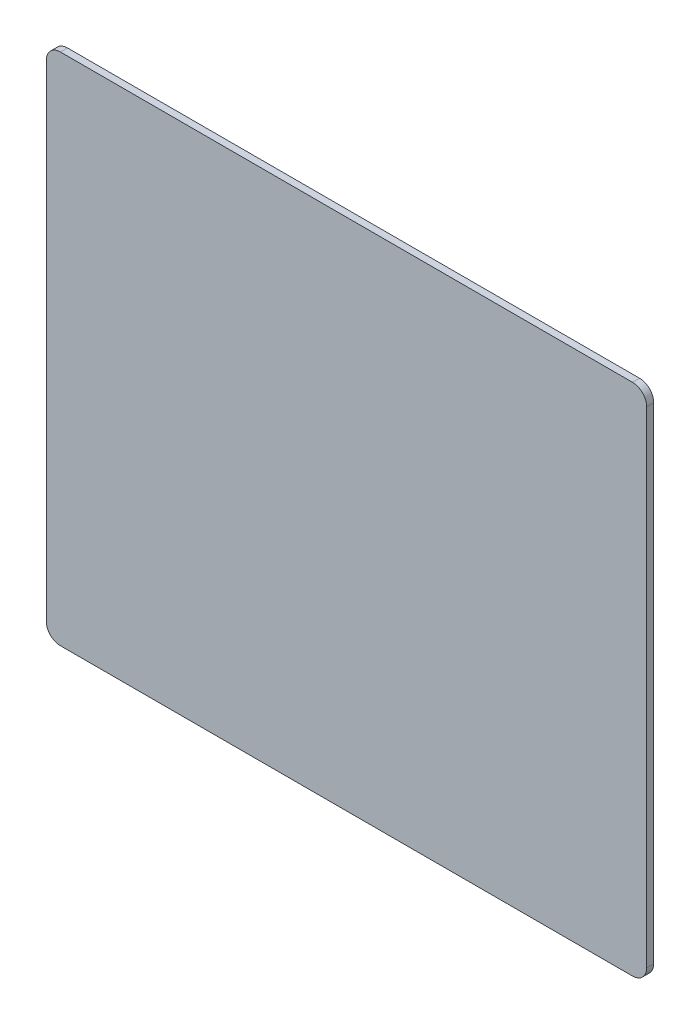
SolidWorks part; units mm, degrees
ref_plane "Plan de face" through (0, 0, 0) normal (0, 0, 1) x (1, 0, 0)
ref_plane "Plan de dessus" through (0, 0, 0) normal (0, 1, 0) x (1, 0, 0)
ref_plane "Plan de droite" through (0, 0, 0) normal (1, 0, 0) x (0, 0, -1)
sketch "Esquisse1" plane through (0, 0, 0) normal (0, 0, 1) x (1, 0, 0)
  line L1 (-40.5, 36.4) -> (40.5, 36.4)
  line L2 (-42.5, 34.4) -> (-42.5, -34.4)
  line L3 (-40.5, -36.4) -> (40.5, -36.4)
  line L4 (42.5, 34.4) -> (42.5, -34.4)
  line L5 (-42.5, 36.4) -> (42.5, -36.4) construction
  line L6 (-42.5, -36.4) -> (42.5, 36.4) construction
  arc A0 (-42.5, -34.4) -> (-40.5, -36.4) centre (-40.5, -34.4) ccw
  arc A1 (40.5, -36.4) -> (42.5, -34.4) centre (40.5, -34.4) ccw
  arc A2 (40.5, 36.4) -> (42.5, 34.4) centre (40.5, 34.4) cw
  arc A3 (-40.5, 36.4) -> (-42.5, 34.4) centre (-40.5, 34.4) ccw
  point P0 (0, 0)
  dimension "D3" = 2
  dimension "D1" = 85
  dimension "D2" = 72.8
extrude "Boss.-Extru.1" add sketch "Esquisse1" along normal blind 1
sketch "Esquisse2" plane through (0, 0, 0) normal (0, 0, -1) x (-1, 0, 0)
  line L0 (-35.5, 28.4) -> (-35.5, 19.4)
  line L1 (-35.5, 19.4) -> (-31.627, 18.4)
  line L2 (-31.627, 18.4) -> (-20.5, 18.4)
  line L3 (-20.5, 18.4) -> (-20.5, 28.4)
  line L4 (-20.5, 28.4) -> (-35.5, 28.4)
  line L5 (-42.5, -34.4) -> (-42.5, 34.4) construction
  line L6 (-40.5, 36.4) -> (40.5, 36.4) construction
  dimension "D1" = 15
  dimension "D2" = 10
  dimension "D3" = 9
  dimension "D4" = 4
  dimension "D5" = 7
  dimension "D6" = 8
extrude "Boss.-Extru.2" add sketch "Esquisse2" along normal blind 0.2
pattern_linear "Répétition linéaire1" count 4 spacing 19 along (-1, 0, 0) count 5 spacing 12 along (0, -1, 0) skipping (3, 3), (3, 4) of "Boss.-Extru.2"
sketch "Esquisse3" plane through (0, 0, 0) normal (0, 0, -1) x (-1, 0, 0)
  line L1 (21.5, -7.6) -> (36.5, -7.6) construction
  line L2 (36.5, -7.6) -> (36.5, -17.6) construction
  line L3 (36.5, -17.6) -> (21.5, -17.6) construction
  line L4 (21.5, -17.6) -> (21.5, -7.6) construction
  line L5 (36.5, -5.6) -> (36.5, 4.4) construction
  line L6 (21.5, 4.4) -> (21.5, -4.6) construction
  line L7 (6.373, -17.6) -> (17.5, -17.6) construction
  line L8 (17.5, -7.6) -> (2.5, -7.6) construction
  ellipse E0 centre (29, -12.6) end of major axis (36.5, -12.6) minor radius 5
  point P18 (36.5, -13.4665)
extrude "Boss.-Extru.3" add sketch "Esquisse3" along normal blind 0.2
pattern_linear "Répétition linéaire2" count 2 spacing 12 along (0, -1, 0) of "Boss.-Extru.3"
sketch "Esquisse4" plane through (0, 0, -0.2) normal (0, 0, -1) x (-1, 0, 0)
  line L0 (-20.5, 18.4) -> (-20.5, 28.4) construction
  line L1 (-31.75, 20.4) -> (-20.5, 20.4) construction
  line L2 (-31.75, 20.4) -> (-31.75, 33.0905) construction
  line L4 (-20.5, 28.4) -> (-35.5, 28.4) construction
  line L5 (-12.75, 20.4) -> (-3.304, 20.4) construction
  line L6 (-1.5, 28.4) -> (-16.5, 28.4) construction
  line L7 (7, 20.4) -> (15.4189, 20.4) construction
  line L8 (27, 18.9) -> (33.7413, 18.9) construction
  line L9 (-30, 8.4) -> (-22.7278, 8.4) construction
  line L10 (-30, -3.6) -> (-22.7278, -3.6) construction
  line L11 (-11, 8.4) -> (-3.304, 8.4) construction
  line L12 (8, 8.4) -> (15.4189, 8.4) construction
  line L13 (24.3298, 8.4) -> (33.7413, 8.4) construction
  line L14 (24.3298, -3.6) -> (33.7413, -3.6) construction
  line L15 (8, -3.6) -> (14.3175, -3.6) construction
  line L16 (-11, -3.6) -> (-4.8059, -3.6) construction
  line L17 (-30, -15.6) -> (-22.7278, -15.6) construction
  line L18 (-11, -15.6) -> (-3.304, -15.6) construction
  line L19 (8, -15.6) -> (14.3175, -15.6) construction
  line L20 (-31.75, -27.6) -> (-23.9293, -27.6) construction
  line L21 (23.5, -15.6) -> (35.7582, -15.6) construction
  line L22 (-11, -27.6) -> (-4.8059, -27.6) construction
  line L23 (6, -27.6) -> (14.3175, -27.6) construction
  line L24 (23.5, -26.6827) -> (31.8102, -26.6827) construction
  line L25 (17.5, 28.4) -> (2.5, 28.4) construction
  line L26 (36.5, 28.4) -> (21.5, 28.4) construction
  line L27 (36.5, 28.4) -> (21.5, 28.4) construction
  line L28 (-20.5, 16.4) -> (-35.5, 16.4) construction
  line L29 (-20.5, 4.4) -> (-35.5, 4.4) construction
  line L30 (-20.5, -7.6) -> (-35.5, -7.6) construction
  line L31 (-20.5, -19.6) -> (-35.5, -19.6) construction
  line L32 (-1.5, 16.4) -> (-16.5, 16.4) construction
  line L33 (17.5, 16.4) -> (2.5, 16.4) construction
  line L34 (28, 8.4) -> (28, 12.4)
  line L35 (28, 12.4) -> (26.5, 12.4)
  line L36 (26.5, 12.4) -> (29, 15.4)
  line L37 (29, 15.4) -> (31.5, 12.4)
  line L38 (31.5, 12.4) -> (30, 12.4)
  line L39 (30, 12.4) -> (30, 8.4)
  line L40 (30, 8.4) -> (28, 8.4)
  line L41 (36.5, 16.4) -> (21.5, 16.4) construction
  line L44 (28, 3.4) -> (28, -0.6)
  line L52 (28, -0.6) -> (26.5, -0.6)
  line L53 (26.5, -0.6) -> (29, -3.6)
  line L54 (29, -3.6) -> (31.5, -0.6)
  line L55 (31.5, -0.6) -> (30, -0.6)
  line L56 (30, -0.6) -> (30, 3.4)
  line L57 (30, 3.4) -> (28, 3.4)
  line L58 (-24, -23.6) -> (-24, -25.6)
  line L59 (-24, -25.6) -> (-28, -25.6)
  line L60 (-28, -25.6) -> (-28, -27.1)
  line L61 (-28, -27.1) -> (-31, -24.6)
  line L62 (-31, -24.6) -> (-28, -22.1)
  line L63 (-28, -22.1) -> (-28, -23.6)
  line L64 (-28, -23.6) -> (-24, -23.6)
  line L65 (6, -23.6) -> (6, -25.6)
  line L66 (6, -25.6) -> (10, -25.6)
  line L67 (10, -25.6) -> (10, -27.1)
  line L68 (10, -27.1) -> (13, -24.6)
  line L69 (13, -24.6) -> (10, -22.1)
  line L70 (10, -22.1) -> (10, -23.6)
  line L71 (10, -23.6) -> (6, -23.6)
  line L72 (-20.5, -19.6) -> (-35.5, -19.6) construction
  line L73 (-20.5, -29.6) -> (-20.5, -19.6) construction
  line L74 (17.5, -19.6) -> (2.5, -19.6) construction
  line L75 (36.5, 4.4) -> (21.5, 4.4) construction
  text T0 "F1" font "Century Gothic" height in points 22
  text T1 "F2" font "Century Gothic" height in points 22
  text T2 "#" font "Century Gothic" height in points 22
  text T3 "*" font "Century Gothic" height in points 22
  text T4 "1" font "Century Gothic" height in points 22
  text T5 "2" font "Century Gothic" height in points 22
  text T6 "3" font "Century Gothic" height in points 22
  text T7 "4" font "Century Gothic" height in points 22
  text T8 "5" font "Century Gothic" height in points 22
  text T9 "6" font "Century Gothic" height in points 22
  text T10 "7" font "Century Gothic" height in points 22
  text T11 "8" font "Century Gothic" height in points 22
  text T12 "9" font "Century Gothic" height in points 22
  text T13 "0" font "Century Gothic" height in points 22
  text T14 "Esc" font "Century Gothic" height in points 20
  text T15 "Ent" font "Century Gothic" height in points 20
  point P10 (-28, 28.4)
  point P14 (-9, 28.4)
  point P54 (10, 28.4)
  point P58 (29, 28.4)
  point P72 (-28, 16.4)
  point P75 (-9, 16.4)
  point P78 (10, 16.4)
  point P87 (29, 16.4)
  point P110 (0, 0)
  point P113 (-28, -19.6)
  point P116 (-20.5, -24.6)
  point P117 (-24, -24.6)
  point P118 (0, 0)
  point P119 (0, 0)
  point P122 (0, 0)
  point P123 (10, -19.6)
  point P126 (29, 4.4)
  point P127 (0, 0)
  dimension "D1" = 3.75
  dimension "D2" = 8
  dimension "D3" = 3.75
  dimension "D4" = 3
  dimension "D5" = 2
  dimension "D6" = 9.5
  dimension "D7" = 8
  dimension "D8" = 8
  dimension "D9" = 8
  dimension "D10" = 8
  dimension "D11" = 2
  dimension "D12" = 2
  dimension "D13" = 2
  dimension "D14" = 7
  dimension "D15" = 2
  dimension "D16" = 1
  dimension "D17" = 4
  dimension "D18" = 5
  dimension "D19" = 2.5
  dimension "D20" = 4
  dimension "D21" = 7
  dimension "D22" = 2
  dimension "D23" = 1
  dimension "D24" = 2
  dimension "D25" = 7
  dimension "D26" = 7
  dimension "D27" = 4
  dimension "D28" = 5
  dimension "D29" = 1
  dimension "D30" = 2.5
  dimension "D31" = 4
  dimension "D32" = 2.5
  dimension "D33" = 5.5
extrude "Boss.-Extru.4" add sketch "Esquisse4" along normal blind 0.2
